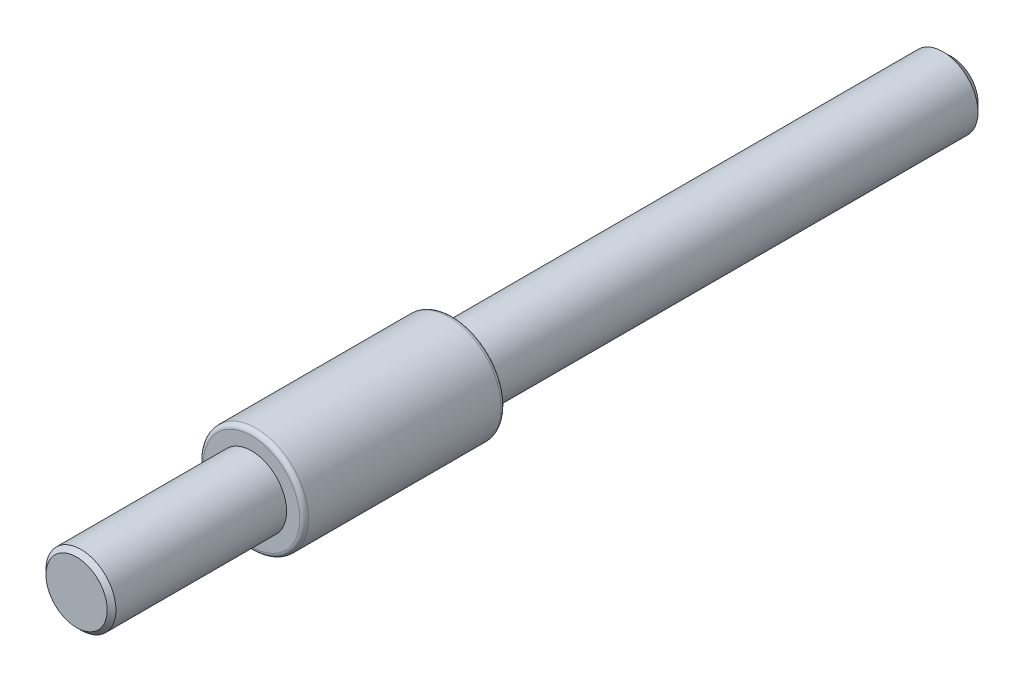
SolidWorks part; units mm, degrees
ref_plane "前视基准面" through (0, 0, 0) normal (0, 0, 1) x (1, 0, 0)
ref_plane "上视基准面" through (0, 0, 0) normal (0, 1, 0) x (1, 0, 0)
ref_plane "右视基准面" through (0, 0, 0) normal (1, 0, 0) x (0, 0, -1)
sketch "草图1" plane through (0, 0, 0) normal (0, 0, 1) x (1, 0, 0)
  circle A0 centre (0, 0) radius 4
  dimension "D1" = 8
extrude "凸台-拉伸1" add sketch "草图1" along normal blind 20
cosmetic thread "装饰螺纹线13" parameters "D1"=20, "D2"=7.8
cosmetic thread "装饰螺纹线14" parameters "D1"=20, "D2"=7.8
sketch "草图2" plane through (0, 0, 0) normal (0, 0, 1) x (1, 0, 0)
  circle A0 centre (0, 0) radius 6
  dimension "D1" = 12
extrude "凸台-拉伸2" add sketch "草图2" against normal blind 23
sketch "草图3" plane through (0, 0, -23) normal (0, 0, -1) x (-1, 0, 0)
  circle A0 centre (0, 0) radius 4
  dimension "D1" = 8
extrude "凸台-拉伸5" add sketch "草图3" along normal blind 57
chamfer "倒角1" distance 1 angle 45 1 edges at (-4, 0, -80)
chamfer "倒角2" distance 0.5 angle 45 1 edges at (4, 0, 20)
fillet "圆角1" radius 0.5 1 edges at (6, 0, -23)
fillet "圆角2" radius 0.5 1 edges at (6, 0, 0)
